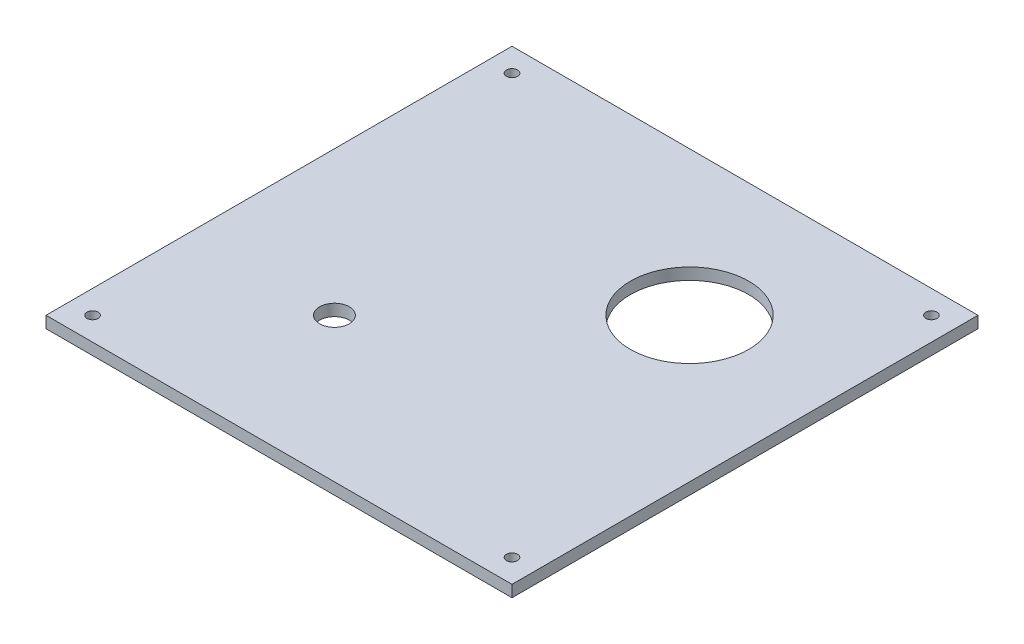
SolidWorks part; units mm, degrees
ref_plane "Front Plane" through (0, 0, 0) normal (0, 0, 1) x (1, 0, 0)
ref_plane "Top Plane" through (0, 0, 0) normal (0, 1, 0) x (1, 0, 0)
ref_plane "Right Plane" through (0, 0, 0) normal (1, 0, 0) x (0, 0, -1)
sketch "Sketch1" plane through (0, 0, 0) normal (0, 1, 0) x (1, 0, 0)
  line L1 (100, -100) -> (-100, -100)
  line L2 (100, -100) -> (100, 100)
  line L3 (100, 100) -> (-100, 100)
  line L4 (-100, -100) -> (-100, 100)
  line L5 (100, -100) -> (-100, 100) construction
  line L6 (100, 100) -> (-100, -100) construction
  point P0 (0, 0)
  dimension "D1" = 200
  dimension "D2" = 200
extrude "Boss-Extrude1" add sketch "Sketch1" along normal mid plane 5
sketch "Sketch2" plane through (0, 2.5, 0) normal (0, 1, 0) x (1, 0, 0)
  line L0 (100, -100) -> (100, 100) construction
  line L1 (100, 100) -> (-100, 100) construction
  line L2 (-100, 100) -> (-100, -100) construction
  line L4 (-100, -100) -> (100, -100) construction
  circle A0 centre (-90, 90) radius 2.3813
  circle A1 centre (90, 90) radius 2.3813
  circle A2 centre (-90, -90) radius 2.3813
  circle A3 centre (90, -90) radius 2.3813
  point P8 (0, 0)
  point P9 (0, 0)
  point P10 (0, 0)
  point P11 (0, 0)
  dimension "D5" = 4.7625
  dimension "D1" = 10
  dimension "D2" = 10
  dimension "D3" = 10
  dimension "D4" = 10
extrude "Cut-Extrude1" cut sketch "Sketch2" against normal blind 5
sketch "Sketch3" plane through (0, 2.5, 0) normal (0, 1, 0) x (1, 0, 0)
  circle A0 centre (-38.1, -38.1) radius 6.35
  dimension "D1" = 12.7
  dimension "D2" = 38.1
  dimension "D3" = 38.1
extrude "Cut-Extrude2" cut sketch "Sketch3" against normal blind 5
sketch "Sketch4" plane through (0, 2.5, 0) normal (0, 1, 0) x (1, 0, 0)
  circle A0 centre (38.1, 38.1) radius 25.4
  dimension "D3" = 50.8
  dimension "D1" = 38.1
  dimension "D2" = 38.1
extrude "Cut-Extrude3" cut sketch "Sketch4" against normal through all
